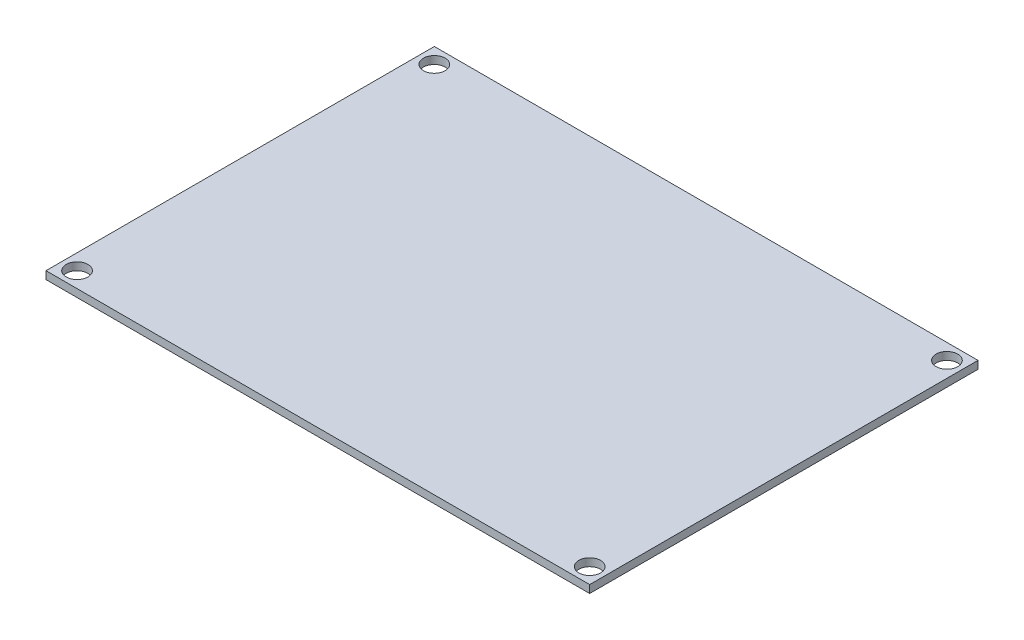
SolidWorks part; units mm, degrees
ref_plane "Front Plane" through (0, 0, 0) normal (0, 0, 1) x (1, 0, 0)
ref_plane "Top Plane" through (0, 0, 0) normal (0, 1, 0) x (1, 0, 0)
ref_plane "Right Plane" through (0, 0, 0) normal (1, 0, 0) x (0, 0, -1)
sketch "Sketch1" plane through (0, 0, 0) normal (0, 1, 0) x (1, 0, 0)
  line L1 (0, 0) -> (70, 0)
  line L2 (0, 0) -> (0, 50)
  line L3 (0, 50) -> (70, 50)
  line L4 (70, 0) -> (70, 50)
  dimension "D1" = 70
  dimension "D2" = 50
extrude "Boss-Extrude1" add sketch "Sketch1" along normal blind 1
sketch "Sketch2" plane through (0, 1, 0) normal (0, 1, 0) x (1, 0, 0)
  line L0 (2, 25) -> (0, 25) construction
  line L1 (2, 48) -> (68, 48) construction
  line L2 (2, 48) -> (2, 2) construction
  line L3 (2, 2) -> (68, 2) construction
  line L4 (68, 48) -> (68, 2) construction
  line L5 (0, 50) -> (0, 0) construction
  line L6 (35, 48) -> (35, 50) construction
  line L7 (70, 50) -> (0, 50) construction
  line L8 (35, 0) -> (35, 2) construction
  line L9 (0, 0) -> (70, 0) construction
  line L10 (68, 25) -> (70, 25) construction
  line L11 (70, 0) -> (70, 50) construction
  circle A0 centre (2, 48) radius 1.4
  circle A1 centre (68, 48) radius 1.4
  circle A2 centre (68, 2) radius 1.4
  circle A3 centre (2, 2) radius 1.4
  dimension "D3" = 2.8
  dimension "D1" = 2
  dimension "D2" = 2
extrude "Cut-Extrude1" cut sketch "Sketch2" against normal through all
